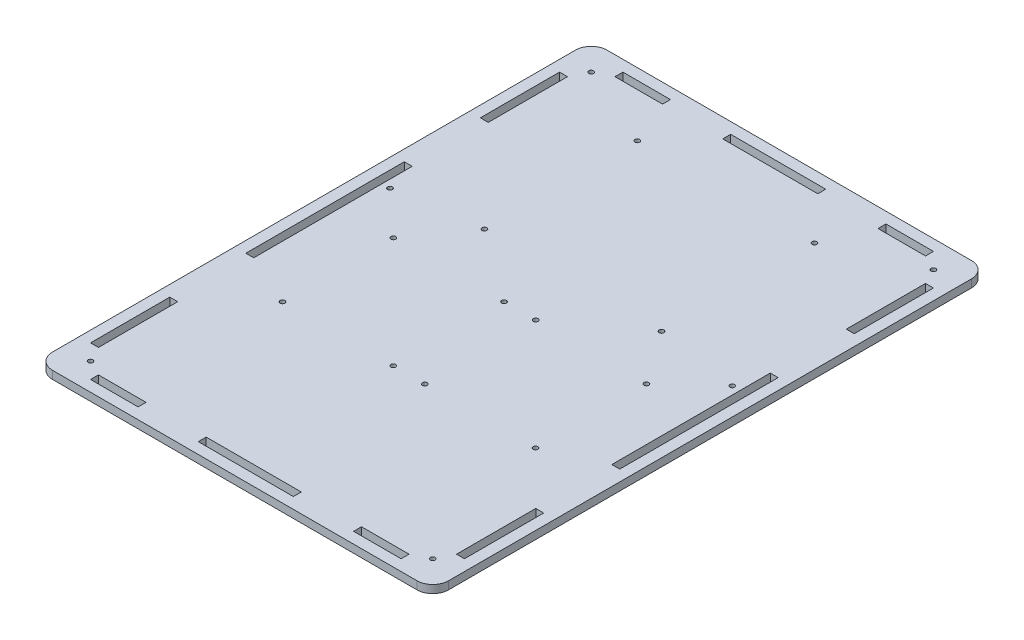
SolidWorks part; units mm, degrees
ref_plane "Front Plane" through (0, 0, 0) normal (0, 0, 1) x (1, 0, 0)
ref_plane "Top Plane" through (0, 0, 0) normal (0, 1, 0) x (1, 0, 0)
ref_plane "Right Plane" through (0, 0, 0) normal (1, 0, 0) x (0, 0, -1)
sketch "Sketch1" plane through (0, 0, 0) normal (0, 1, 0) x (1, 0, 0)
  line L0 (125, 350) -> (125, 0) construction
  line L1 (10, 0) -> (240, 0)
  line L2 (0, 10) -> (0, 340)
  line L3 (10, 350) -> (240, 350)
  line L4 (250, 10) -> (250, 340)
  line L5 (0, 175) -> (250, 175) construction
  line L13 (57, 343) -> (27, 343)
  line L14 (125, 343) -> (95, 343)
  line L15 (7, 323) -> (12, 323)
  line L16 (7, 323) -> (7, 273)
  line L17 (7, 273) -> (12, 273)
  line L18 (12, 323) -> (12, 273)
  line L19 (7, 225) -> (12, 225)
  line L20 (7, 225) -> (7, 175)
  line L22 (12, 225) -> (12, 125)
  line L23 (95, 343) -> (95, 338)
  line L24 (95, 338) -> (155, 338)
  line L25 (27, 343) -> (27, 338)
  line L26 (27, 338) -> (57, 338)
  line L27 (57, 338) -> (57, 343)
  line L28 (95, 12) -> (155, 12)
  line L29 (95, 7) -> (95, 12)
  line L30 (57, 12) -> (57, 7)
  line L31 (27, 12) -> (57, 12)
  line L32 (27, 7) -> (27, 12)
  line L33 (7, 77) -> (12, 77)
  line L34 (12, 27) -> (12, 77)
  line L35 (7, 27) -> (12, 27)
  line L36 (7, 125) -> (12, 125)
  line L37 (155, 7) -> (155, 12)
  line L38 (193, 12) -> (193, 7)
  line L39 (223, 7) -> (223, 12)
  line L40 (223, 12) -> (193, 12)
  line L41 (243, 27) -> (238, 27)
  line L42 (238, 27) -> (238, 77)
  line L43 (243, 77) -> (238, 77)
  line L44 (243, 125) -> (238, 125)
  line L45 (238, 225) -> (238, 125)
  line L46 (243, 225) -> (238, 225)
  line L47 (243, 273) -> (238, 273)
  line L48 (238, 323) -> (238, 273)
  line L49 (243, 323) -> (238, 323)
  line L50 (223, 343) -> (223, 338)
  line L51 (223, 338) -> (193, 338)
  line L52 (193, 338) -> (193, 343)
  line L53 (155, 343) -> (155, 338)
  line L54 (155, 343) -> (125, 343)
  line L55 (193, 343) -> (223, 343)
  line L56 (243, 323) -> (243, 273)
  line L57 (243, 225) -> (243, 125)
  line L58 (243, 77) -> (243, 27)
  line L59 (223, 7) -> (193, 7)
  line L60 (155, 7) -> (95, 7)
  line L61 (27, 7) -> (57, 7)
  line L62 (7, 27) -> (7, 77)
  line L63 (7, 175) -> (7, 125)
  circle A0 centre (69.12, 310) radius 1.5
  circle A1 centre (180.88, 310) radius 1.5
  circle A2 centre (180.88, 213.48) radius 1.5
  circle A3 centre (69.12, 213.48) radius 1.5
  circle A4 centre (45.15, 179.98) radius 1.5
  circle A5 centre (115, 179.98) radius 1.5
  circle A6 centre (45.15, 110) radius 1.5
  circle A7 centre (115, 110) radius 1.5
  circle A8 centre (135, 110) radius 1.5
  circle A9 centre (204.85, 110) radius 1.5
  circle A10 centre (135, 179.98) radius 1.5
  circle A11 centre (204.85, 179.98) radius 1.5
  arc A12 (10, 0) -> (0, 10) centre (10, 10) cw
  arc A13 (250, 10) -> (240, 0) centre (240, 10) cw
  arc A14 (250, 340) -> (240, 350) centre (240, 340) ccw
  arc A15 (0, 340) -> (10, 350) centre (10, 340) cw
  circle A16 centre (17, 333) radius 1.5
  circle A17 centre (233, 333) radius 1.5
  circle A18 centre (17, 17) radius 1.5
  circle A19 centre (233, 17) radius 1.5
  circle A22 centre (17, 206) radius 1.5
  circle A23 centre (233, 206) radius 1.5
  point P12 (125, 236.48)
  point P13 (125, 333)
  point P33 (125, 175)
  point P38 (0, 0)
  point P68 (12, 175)
  point P69 (250, 0)
  point P72 (125, 12)
  point P94 (125, 338)
  point P99 (0, 350)
  dimension "D6" = 69.98
  dimension "D7" = 69.98
  dimension "D14" = 10
  dimension "D21" = 31
  dimension "D1" = 350
  dimension "D2" = 250
  dimension "D3" = 69.85
  dimension "D4" = 69.85
  dimension "D5" = 20
  dimension "D8" = 69.98
  dimension "D9" = 69.98
  dimension "D10" = 110
  dimension "D11" = 111.76
  dimension "D12" = 96.52
  dimension "D13" = 40
  dimension "D15" = 17
  dimension "D16" = 5
  dimension "D17" = 17
  dimension "D18" = 50
  dimension "D19" = 5
  dimension "D20" = 50
  dimension "D22" = 30
  dimension "D23" = 5
  dimension "D24" = 5
  dimension "D25" = 30
  dimension "D26" = 5
extrude "Boss-Extrude1" add sketch "Sketch1" along normal blind 5
